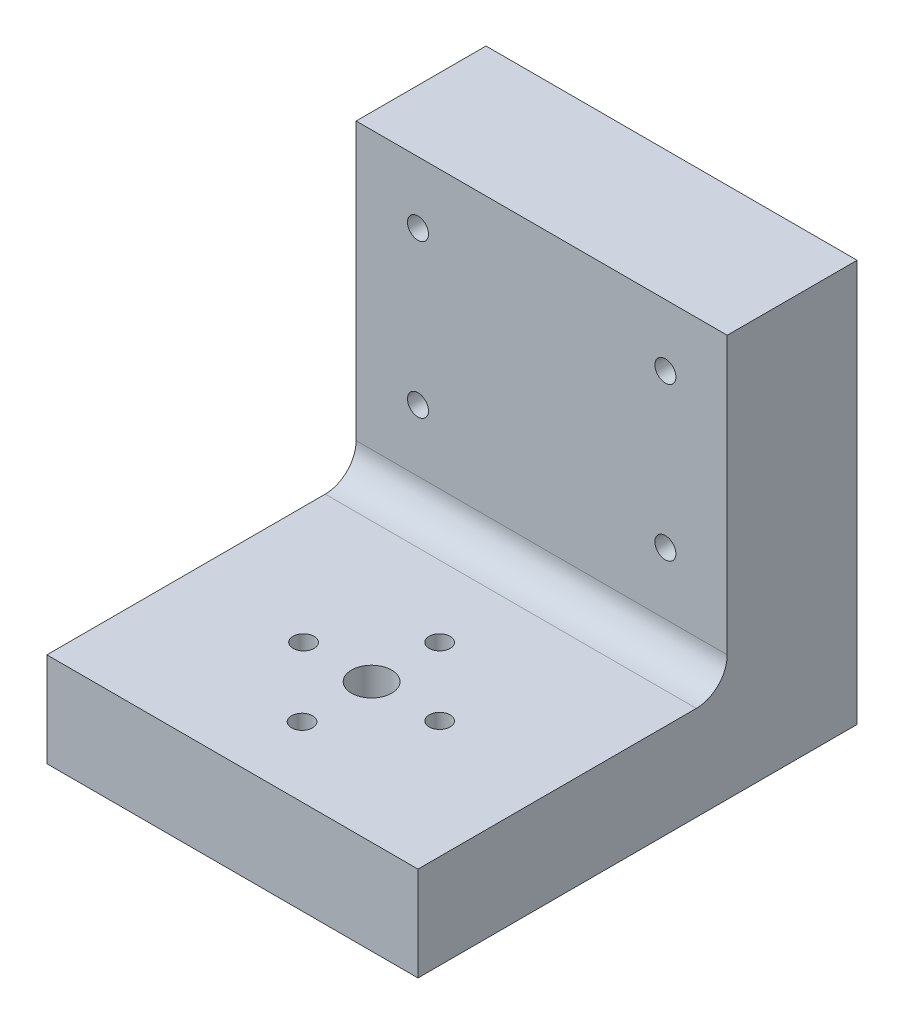
SolidWorks part; units mm, degrees
material "PLA"
ref_plane "Front Plane" through (0, 0, 0) normal (0, 0, 1) x (1, 0, 0)
ref_plane "Top Plane" through (0, 0, 0) normal (0, 1, 0) x (1, 0, 0)
ref_plane "Right Plane" through (0, 0, 0) normal (1, 0, 0) x (0, 0, -1)
sketch "Sketch1" plane through (0, 0, 0) normal (0, 0, 1) x (1, 0, 0)
  line L1 (-52.9116, 35.8689) -> (7.0884, 35.8689)
  line L2 (-52.9116, 35.8689) -> (-52.9116, -29.1311)
  line L3 (-52.9116, -29.1311) -> (7.0884, -29.1311)
  line L4 (7.0884, 35.8689) -> (7.0884, -29.1311)
  dimension "D1" = 65
  dimension "D2" = 60
extrude "Boss-Extrude1" add sketch "Sketch1" along normal blind 21
sketch "Sketch2" plane through (0, -29.1311, 0) normal (0, -1, 0) x (1, 0, 0)
  line L1 (-52.9116, 21) -> (7.0884, 21)
  line L2 (-52.9116, 21) -> (-52.9116, 71)
  line L3 (-52.9116, 71) -> (7.0884, 71)
  line L4 (7.0884, 21) -> (7.0884, 71)
  dimension "D1" = 50
extrude "Boss-Extrude2" add sketch "Sketch2" against normal blind 15.25 contours L2 L1 L4 L3
fillet "Fillet1" radius 5 1 edges at (-22.9116, -13.8811, 21)
sketch "Sketch3" plane through (0, -13.8811, 0) normal (0, 1, 0) x (1, 0, 0)
  circle A0 centre (-22.9116, -48.5) radius 3.25
  circle A1 centre (-22.9116, -48.5) radius 11 construction
  circle A2 centre (-11.9116, -48.5) radius 1.7
  circle A3 centre (-22.9116, -59.75) radius 1.7
  circle A4 centre (-33.9116, -48.5) radius 1.7
  circle A5 centre (-22.9116, -37.5) radius 1.7
  point P6 (-22.9116, -48.5)
  point P7 (-11.9116, -48.5)
  point P9 (-22.9116, -59.75)
  point P11 (-33.9116, -48.5)
  point P13 (-22.9116, -37.5)
  dimension "D1" = 6.5
  dimension "D2" = 22
  dimension "D3" = 3.4
  dimension "D4" = 3.4
  dimension "D5" = 3.4
  dimension "D6" = 3.4
extrude "Cut-Extrude4" cut sketch "Sketch3" against normal blind 15.25
sketch "Sketch10" plane through (0, 0, 21) normal (0, 0, 1) x (1, 0, 0)
  circle A0 centre (-2.9116, 25.8689) radius 1.7
  circle A1 centre (-2.9116, 1.1189) radius 1.7
  circle A2 centre (-42.9116, 25.8689) radius 1.7
  circle A3 centre (-42.9116, 1.1189) radius 1.7
  dimension "D1" = 3.4
  dimension "D2" = 3.4
  dimension "D3" = 3.4
  dimension "D4" = 3.4
extrude "Cut-Extrude5" cut sketch "Sketch10" against normal blind 21
equation "\"PCD\"= 22mm"
equation "\"h\"= 15.25mm"
equation "\"t\"= 21mm"
equation "\"b\"= 60mm"
equation "\"l\"= 50mm"
equation "\"l2\"= 65mm"
equation "\"Shaft hole\"= 6.5mm"
equation "\"bolt hole\"= 3.4mm"
equation "\"fillet R\"= 5mm"
